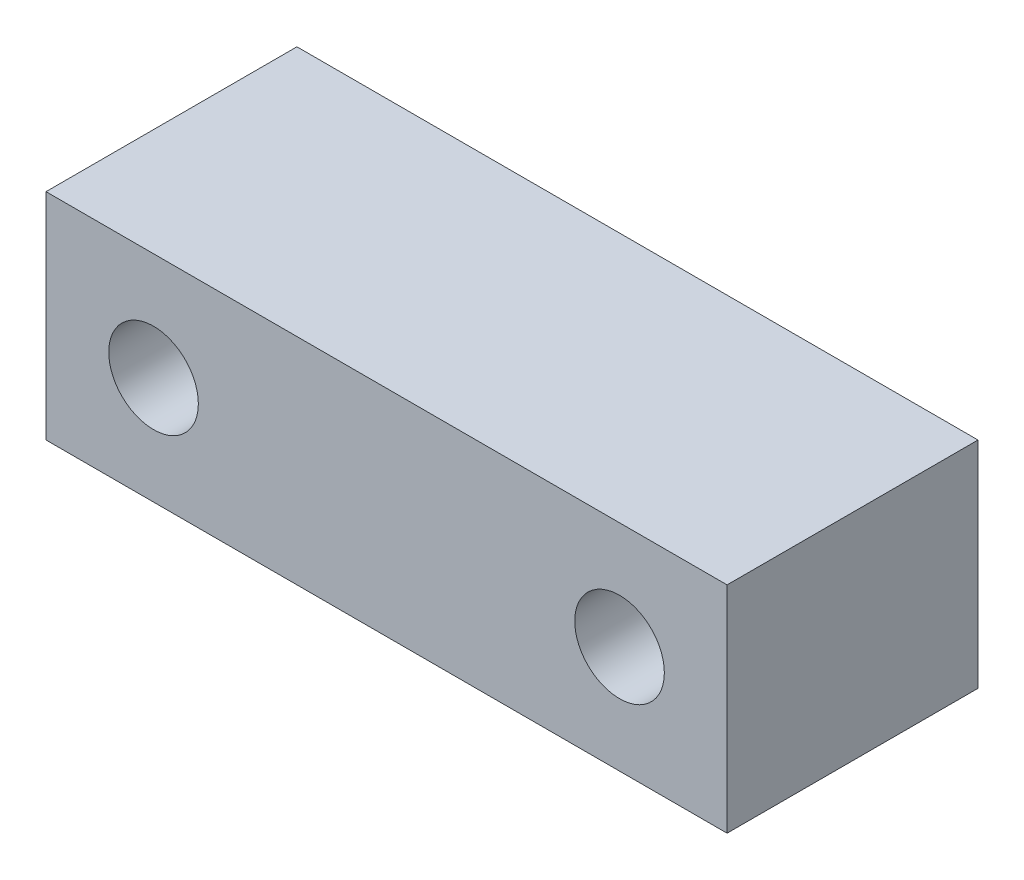
SolidWorks part; units mm, degrees
ref_plane "Front Plane" through (0, 0, 0) normal (1, 0, 0) x (0, 1, 0)
ref_plane "Top Plane" through (0, 0, 0) normal (0, 0, 1) x (0, 1, 0)
ref_plane "Right Plane" through (0, 0, 0) normal (0, 1, 0) x (-1, 0, 0)
sketch "Sketch1" plane through (0, 0, 0) normal (0, 0, 1) x (0, 1, 0)
  line L1 (-3, 9.5) -> (3, 9.5)
  line L2 (-3, 9.5) -> (-3, -9.5)
  line L3 (-3, -9.5) -> (3, -9.5)
  line L4 (3, 9.5) -> (3, -9.5)
  line L5 (-3, 9.5) -> (3, -9.5) construction
  line L6 (-3, -9.5) -> (3, 9.5) construction
  circle A0 centre (0, 6.5) radius 1.25
  circle A1 centre (0, -6.5) radius 1.25
  point P0 (0, 0)
  dimension "D3" = 2.5
  dimension "D4" = 2.5
  dimension "D5" = 3
  dimension "D6" = 3
  dimension "D7" = 3
  dimension "D1" = 19
  dimension "D2" = 6
  dimension "D8" = 3
extrude "Boss-Extrude1" add sketch "Sketch1" along normal blind 7
